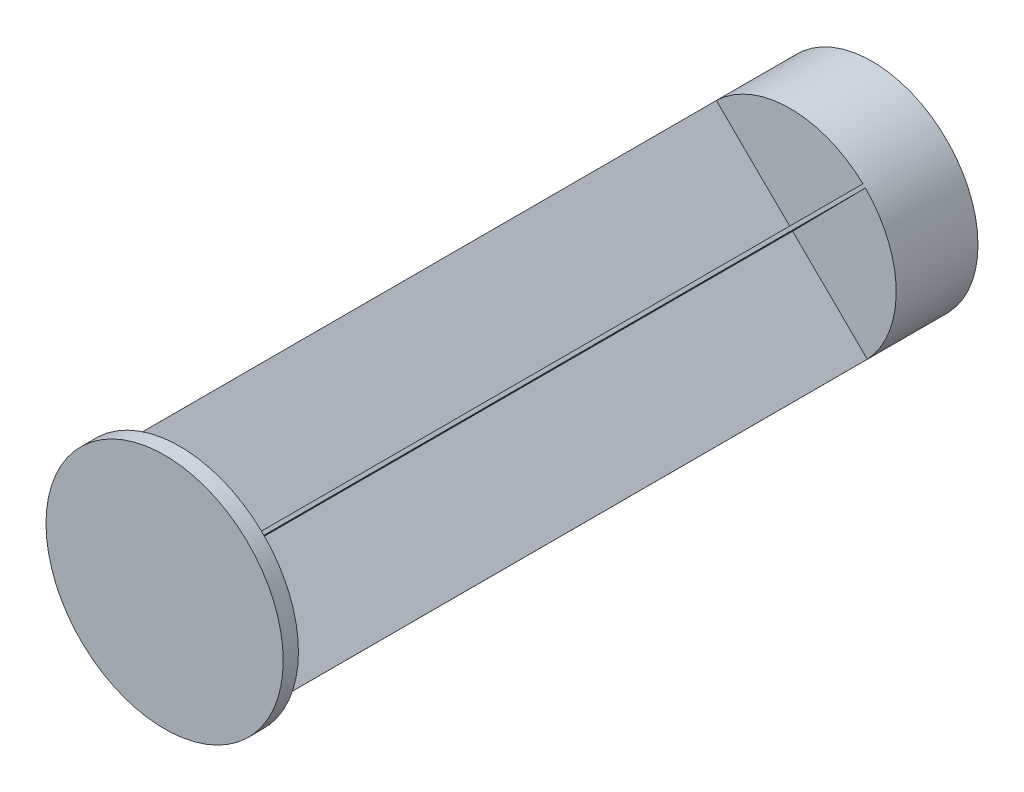
SolidWorks part; units mm, degrees
ref_plane "Płaszczyzna przednia" through (0, 0, 0) normal (0, 0, 1) x (1, 0, 0)
ref_plane "Płaszczyzna górna" through (0, 0, 0) normal (0, 1, 0) x (1, 0, 0)
ref_plane "Płaszczyzna prawa" through (0, 0, 0) normal (1, 0, 0) x (0, 0, -1)
sketch "Sketch1" plane through (0, 0, 0) normal (0, 0, 1) x (1, 0, 0)
  circle A0 centre (0, 0) radius 23.31
  dimension "D1" = 46.62
extrude "Boss-Extrude1" add sketch "Sketch1" along normal blind 15
sketch "Sketch2" plane through (0, 0, 15) normal (0, 0, 1) x (1, 0, 0)
  circle A0 centre (0, 0) radius 23.31
extrude "Boss-Extrude2" add sketch "Sketch2" along normal blind 3
sketch "Sketch3" plane through (0, 0, 18) normal (0, 0, 1) x (1, 0, 0)
  line L0 (0, 0) -> (-16.6064, 16.358) construction
  line L1 (-16.6064, 16.358) -> (16.6064, -16.358) construction
  line L2 (0, 0) -> (16.358, 16.6064) construction
  line L3 (16.358, 16.6064) -> (-16.358, -16.6064) construction
  line L4 (-19.7382, 18.7411) -> (-19.0009, 19.4185)
  line L5 (-19.0009, 19.4185) -> (21.6253, -20.6)
  line L6 (21.6253, -20.6) -> (20.9236, -21.3124)
  line L7 (20.9236, -21.3124) -> (-19.7382, 18.7411)
  line L8 (-20.349, -19.9455) -> (-19.8147, -20.4718)
  line L9 (-19.8147, -20.4718) -> (21.4547, 21.4243)
  line L10 (21.4547, 21.4243) -> (20.9204, 21.9506)
  line L11 (20.9204, 21.9506) -> (-20.349, -19.9455)
  circle A0 centre (0, 0) radius 23.31 construction
  circle A1 centre (0, 0) radius 23.31
  circle M13 centre (0, 0) radius 23.31
  dimension "D1" = 0.5
  dimension "D2" = 0.5
  dimension "D3" = 0.5
  dimension "D4" = 0.5
extrude "Boss-Extrude5" add sketch "Sketch3" along normal blind 134.3 contours L11 L5 L7 M13 | L11 L5 L9 M13 | L7 L11 L9 M13 | L9 L7 L5 M13
sketch "Sketch4" plane through (0, 0, 18) normal (0, 0, 1) x (1, 0, 0)
  circle A0 centre (0, 0) radius 23.31
extrude "Cut-Extrude2" cut sketch "Sketch4" along normal blind 204 flip side to cut
sketch "Sketch5" plane through (0, 0, 152.3) normal (0, 0, 1) x (1, 0, 0)
  circle A0 centre (0, 0) radius 26.095
  dimension "D1" = 52.19
extrude "Boss-Extrude6" add sketch "Sketch5" along normal blind 3.35
